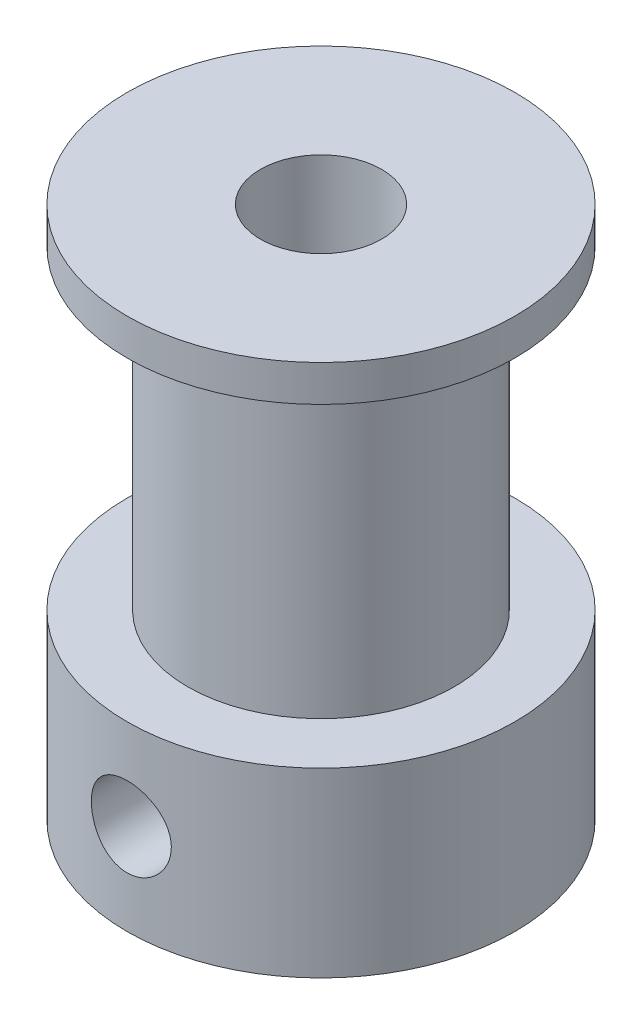
SolidWorks part; units mm, degrees
material "aluminio"
ref_plane "Alzado" through (0, 0, 0) normal (0, 0, 1) x (1, 0, 0)
ref_plane "Planta" through (0, 0, 0) normal (0, 1, 0) x (1, 0, 0)
ref_plane "Vista lateral" through (0, 0, 0) normal (1, 0, 0) x (0, 0, -1)
sketch "Croquis1" plane through (0, 0, 0) normal (0, 0, 1) x (1, 0, 0)
  line L0 (0, 0) -> (0, 36.7556) construction
  line L2 (8, 7.5) -> (8, 0)
  line L3 (2.5, 22) -> (8, 22)
  line L4 (8, 22) -> (8, 20.5)
  line L5 (8, 20.5) -> (5.5, 20.5)
  line L6 (5.5, 20.5) -> (5.5, 7.5)
  line L7 (5.5, 7.5) -> (8, 7.5)
  line L9 (8, 0) -> (2.5, 0)
  line L10 (2.5, 0) -> (2.5, 22)
  dimension "D1" = 1.5
  dimension "D2" = 7.5
  dimension "D4" = 5
  dimension "D5" = 11
  dimension "D6" = 16
  dimension "D11" = 13
revolve "Revolución1" add sketch "Croquis1" angle 360 about L0
hole_wizard "Taladro roscado M41" positions "Croquis4" profile "Croquis3" tap size "M4" standard "ISO"
sketch "Croquis4" plane through (0, 0, 0) normal (0, 0, 1) x (1, 0, 0)
  line L1 (0, 0) -> (0, 7.5) construction
  line L2 (8, 7.5) -> (-8, 7.5) construction
  point P2 (0, 3.75)
sketch "Croquis3" plane through (0, 3.75, 0) normal (1, 0, 0) x (0, 1, 0)
  line L0 (0, 0) -> (0, 8.001)
  line L1 (0, 8.001) -> (1.65, 8.001)
  line L2 (1.65, 8.001) -> (1.65, 0)
  line L5 (1.65, 0) -> (0, 0)
  line L11 (0, -6.35) -> (0, 107.95) construction
  dimension "Diámetro de perforador para roscar hasta el siguiente" = 3.3
  dimension "Profundidad de perforador para roscar hasta el siguiente" = 8.001
cosmetic thread "Rosca de taladro3" parameters "D2"=4
cosmetic thread "Rosca cosmética2" parameters "D2"=4
pattern_circular "MatrizC1" count 2 over 90 about axis through (0, 0, 0) along (0, -1, 0) of "Taladro roscado M41"
cosmetic thread "Rosca cosmética1" parameters "D2"=4
